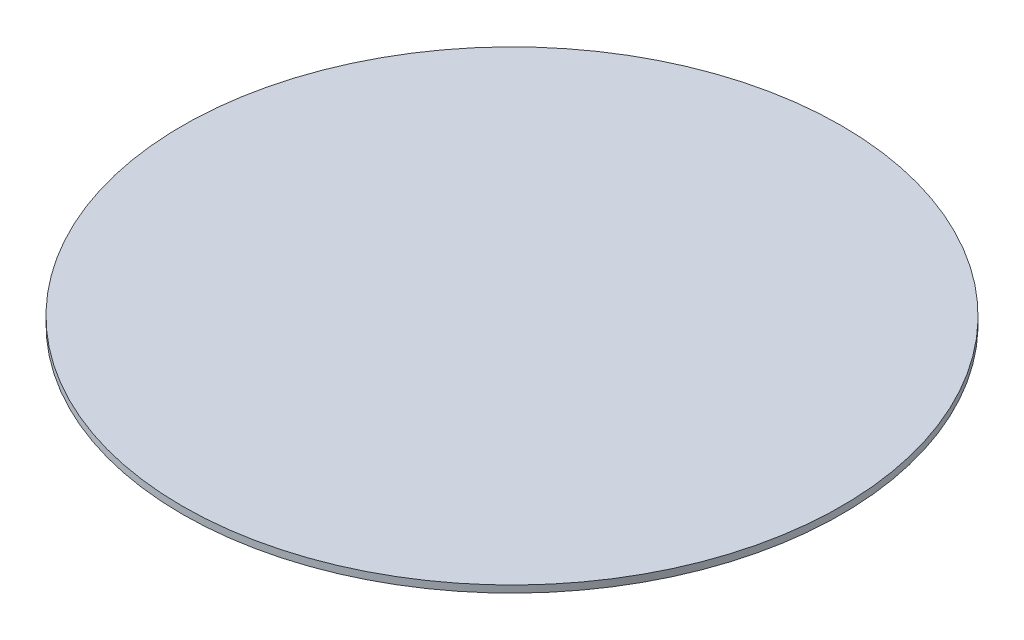
SolidWorks part; units mm, degrees
ref_plane "Front Plane" through (0, 0, 0) normal (0, 0, 1) x (1, 0, 0)
ref_plane "Top Plane" through (0, 0, 0) normal (0, 1, 0) x (1, 0, 0)
ref_plane "Right Plane" through (0, 0, 0) normal (1, 0, 0) x (0, 0, -1)
sketch "Sketch1" plane through (0, 0, 0) normal (0, 1, 0) x (1, 0, 0)
  circle A0 centre (0, 0) radius 60
  dimension "D1" = 120
extrude "Boss-Extrude1" add sketch "Sketch1" along normal blind 1.28
